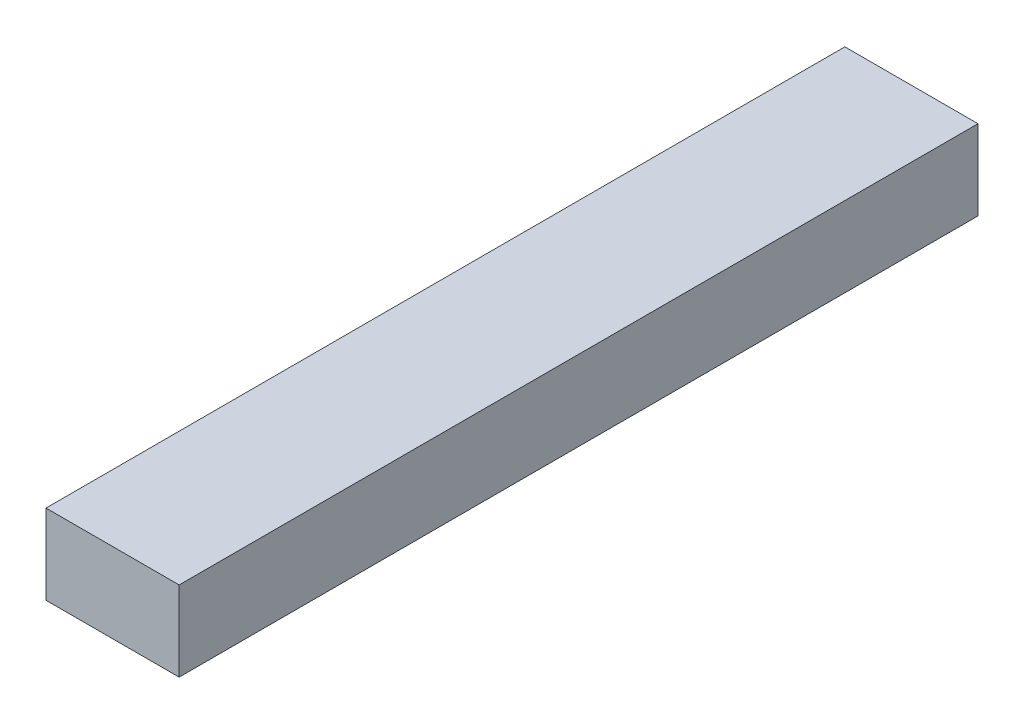
SolidWorks part; units mm, degrees
ref_plane "Front Plane" through (0, 0, 0) normal (0, 0, 1) x (1, 0, 0)
ref_plane "Top Plane" through (0, 0, 0) normal (0, 1, 0) x (1, 0, 0)
ref_plane "Right Plane" through (0, 0, 0) normal (1, 0, 0) x (0, 0, -1)
sketch "Sketch1" plane through (0, 0, 0) normal (0, 0, 1) x (1, 0, 0)
  line L1 (0, 0) -> (-50, 0)
  line L2 (0, 0) -> (0, 30)
  line L3 (0, 30) -> (-50, 30)
  line L4 (-50, 0) -> (-50, 30)
  dimension "D1" = 50
  dimension "D2" = 30
extrude "Boss-Extrude1" add sketch "Sketch1" along normal blind 300
